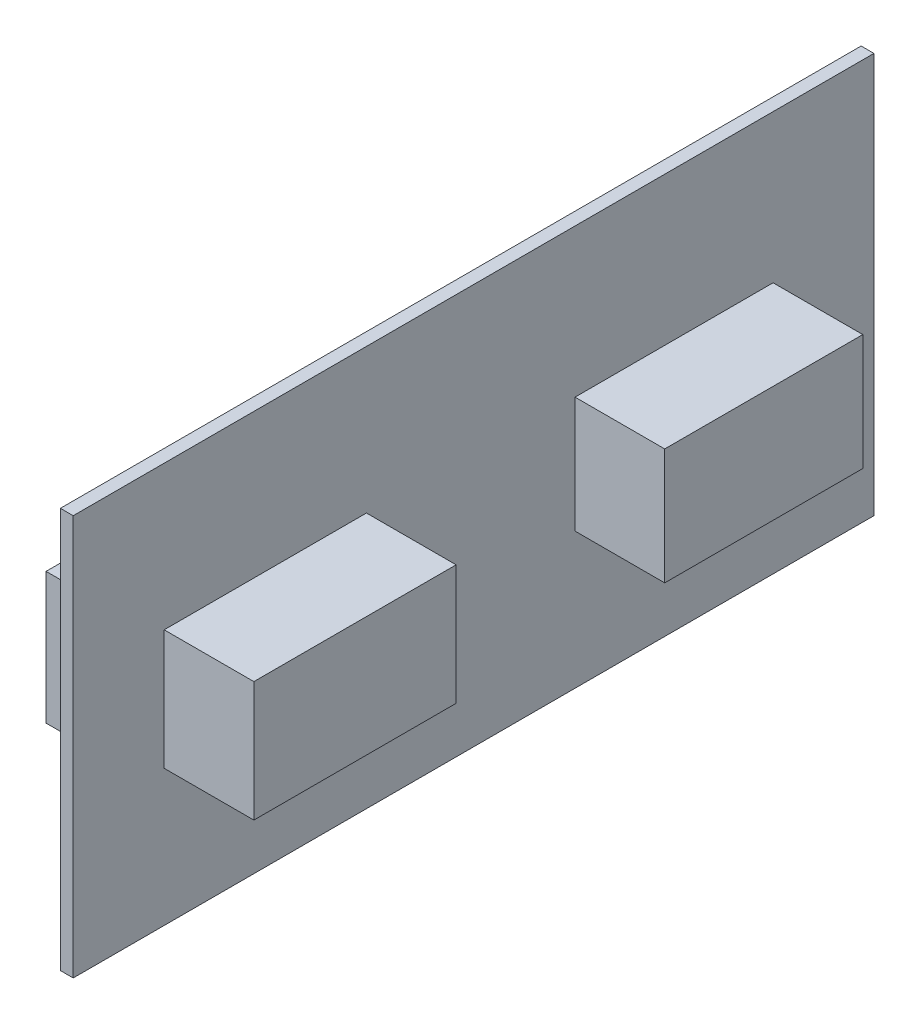
SolidWorks part; units mm, degrees
ref_plane "Alzado" through (0, 0, 0) normal (0, 0, 1) x (1, 0, 0)
ref_plane "Planta" through (0, 0, 0) normal (0, 1, 0) x (1, 0, 0)
ref_plane "Vista lateral" through (0, 0, 0) normal (1, 0, 0) x (0, 0, -1)
sketch "Croquis1" plane through (0, 0, 0) normal (1, 0, 0) x (0, 0, -1)
  line L1 (0, 0) -> (-500, 0)
  line L2 (0, 0) -> (0, 250)
  line L3 (0, 250) -> (-500, 250)
  line L4 (-500, 0) -> (-500, 250)
  dimension "D1" = 500
  dimension "D2" = 250
extrude "Saliente-Extruir1" add sketch "Croquis1" along normal blind 8
sketch "Croquis2" plane through (0, 0, 0) normal (-1, 0, 0) x (0, 0, 1)
  line L1 (56.1403, 164.379) -> (183.0075, 164.379)
  line L2 (56.1403, 164.379) -> (56.1403, 82.2983)
  line L3 (56.1403, 82.2983) -> (183.0075, 82.2983)
  line L4 (183.0075, 164.379) -> (183.0075, 82.2983)
  line L5 (309.611, 164.379) -> (452.9569, 164.379)
  line L6 (309.611, 164.379) -> (309.611, 82.2983)
  line L7 (309.611, 82.2983) -> (452.9569, 82.2983)
  line L8 (452.9569, 164.379) -> (452.9569, 82.2983)
extrude "Saliente-Extruir2" add sketch "Croquis2" along normal blind 56
sketch "Croquis3" plane through (8, 0, 0) normal (1, 0, 0) x (0, 0, -1)
  line L1 (-443.1949, 84.9918) -> (-316.8948, 84.9918)
  line L2 (-443.1949, 84.9918) -> (-443.1949, 159.8906)
  line L3 (-443.1949, 159.8906) -> (-316.8948, 159.8906)
  line L4 (-316.8948, 84.9918) -> (-316.8948, 159.8906)
sketch "Croquis4" plane through (0, 0, 0) normal (-1, 0, 0) x (0, 0, 1)
  line L1 (183.0075, 164.379) -> (56.1403, 164.379)
  line L2 (183.0075, 164.379) -> (183.0075, 82.2983)
  line L3 (183.0075, 82.2983) -> (56.1403, 82.2983)
  line L4 (56.1403, 164.379) -> (56.1403, 82.2983)
  point P7 (454.563, 242.1097)
sketch "Croquis5" plane through (8, 0, 0) normal (1, 0, 0) x (0, 0, -1)
extrude "Saliente-Extruir4" add sketch "Croquis4" along normal blind 56
sketch "Croquis6" plane through (8, 0, 0) normal (1, 0, 0) x (0, 0, -1)
  line L1 (-316.8948, 84.9918) -> (-443.1949, 84.9918)
  line L2 (-316.8948, 84.9918) -> (-316.8948, 159.8906)
  line L3 (-316.8948, 159.8906) -> (-443.1949, 159.8906)
  line L4 (-443.1949, 84.9918) -> (-443.1949, 159.8906)
extrude "Saliente-Extruir5" add sketch "Croquis6" along normal blind 56
sketch "Croquis7" plane through (8, 0, 0) normal (1, 0, 0) x (0, 0, -1)
  line L1 (-186.6448, 84.9918) -> (-62.9639, 84.9918)
  line L2 (-186.6448, 84.9918) -> (-186.6448, 157.4356)
  line L3 (-186.6448, 157.4356) -> (-62.9639, 157.4356)
  line L4 (-62.9639, 84.9918) -> (-62.9639, 157.4356)
  point P4 (-260.9125, 300.4709)
extrude "Saliente-Extruir6" add sketch "Croquis7" along normal blind 56
